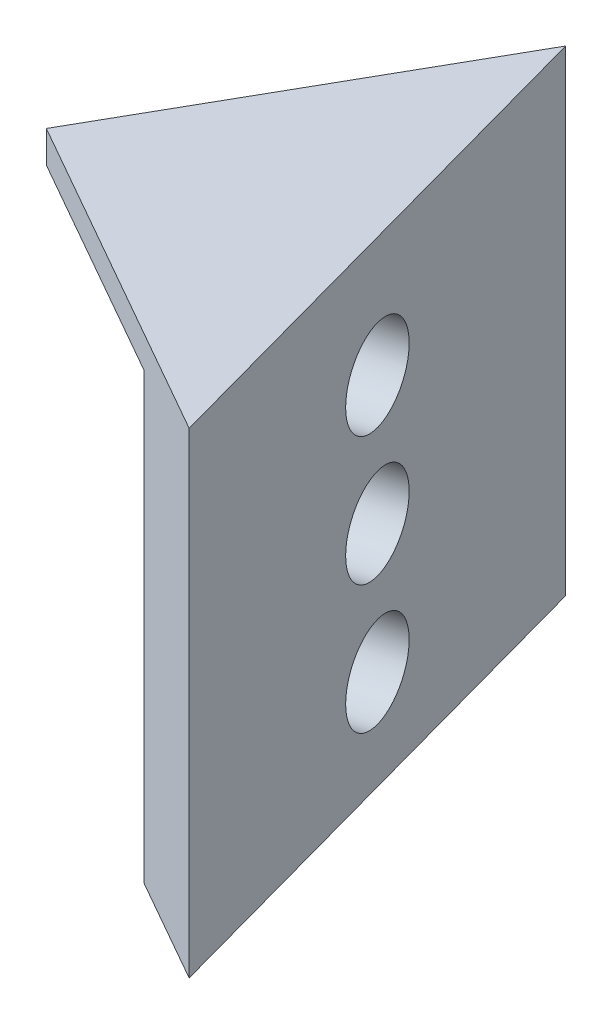
SolidWorks part; units mm, degrees
ref_plane "Front Plane" through (0, 0, 0) normal (0, 0, 1) x (1, 0, 0)
ref_plane "Top Plane" through (0, 0, 0) normal (0, 1, 0) x (1, 0, 0)
ref_plane "Right Plane" through (0, 0, 0) normal (1, 0, 0) x (0, 0, -1)
sketch "Sketch1" plane through (0, 0, 0) normal (0, 1, 0) x (1, 0, 0)
  line L0 (0, 0) -> (264.961, -150.661)
  line L1 (0, 0) -> (150.661, 264.961)
  line L2 (264.961, -150.661) -> (150.661, 264.961)
  dimension "D1" = 45
  dimension "D2" = 90
  dimension "D3" = 45
  dimension "D4" = 114.3
  dimension "D5" = 304.8
  dimension "D6" = 304.8
extrude "Boss-Extrude1" add sketch "Sketch1" along normal blind 25.4
sketch "Sketch2" plane through (0, 25.4, 0) normal (0, 1, 0) x (1, 0, 0)
  line L0 (150.661, 264.961) -> (102.9377, 181.0322)
  line L1 (150.661, 264.961) -> (0, 0) construction
  line L2 (150.661, 264.961) -> (264.961, -150.661)
  line L3 (264.961, -150.661) -> (150.661, 264.961) construction
  line L4 (0, 0) -> (264.961, -150.661) construction
  line L5 (264.961, -150.661) -> (181.0322, -102.9377)
  line L6 (181.0322, -102.9377) -> (102.9377, 181.0322)
  point P5 (8.2325, 85.8689)
  point P12 (74.8017, -7.1715)
extrude "Boss-Extrude2" add sketch "Sketch2" against normal blind 381
sketch "Sketch3" plane through (141.9849, 0, -39.0472) normal (-0.9642, 0, 0.2652) x (0.2652, 0, 0.9642)
  line L0 (0, -70.2908) -> (147.2563, -70.2908) construction
  line L1 (147.2563, -355.6) -> (147.2563, 0) construction
  line L2 (0, -70.2908) -> (-147.2563, -70.2908) construction
  line L3 (-147.2563, -355.6) -> (-147.2563, 0) construction
  line L4 (0, -275.9584) -> (-147.2563, -275.9584) construction
  line L5 (0, -173.1246) -> (147.2563, -173.1246) construction
  line L6 (0, -173.1246) -> (-147.2563, -173.1246) construction
  line L7 (0, -275.9584) -> (147.2563, -275.9584) construction
  line L8 (-147.2563, -70.2908) -> (-147.2563, -173.1246) construction
  line L9 (-147.2563, -173.1246) -> (-147.2563, -275.9584) construction
  line L10 (147.2563, -70.2908) -> (147.2563, -173.1246) construction
  line L11 (147.2563, -173.1246) -> (147.2563, -275.9584) construction
  circle A0 centre (0, -70.2908) radius 36.3535
  circle A1 centre (0, -173.1246) radius 36.3535
  circle A2 centre (0, -275.9584) radius 36.3535
  point P16 (0, -83.368)
  point P17 (0, -275.9584)
  point P18 (0, 0)
  point P19 (0, -70.2908)
  point P20 (0, 0)
  point P21 (0, -275.9584)
extrude "Cut-Extrude1" cut sketch "Sketch3" against normal blind 381
